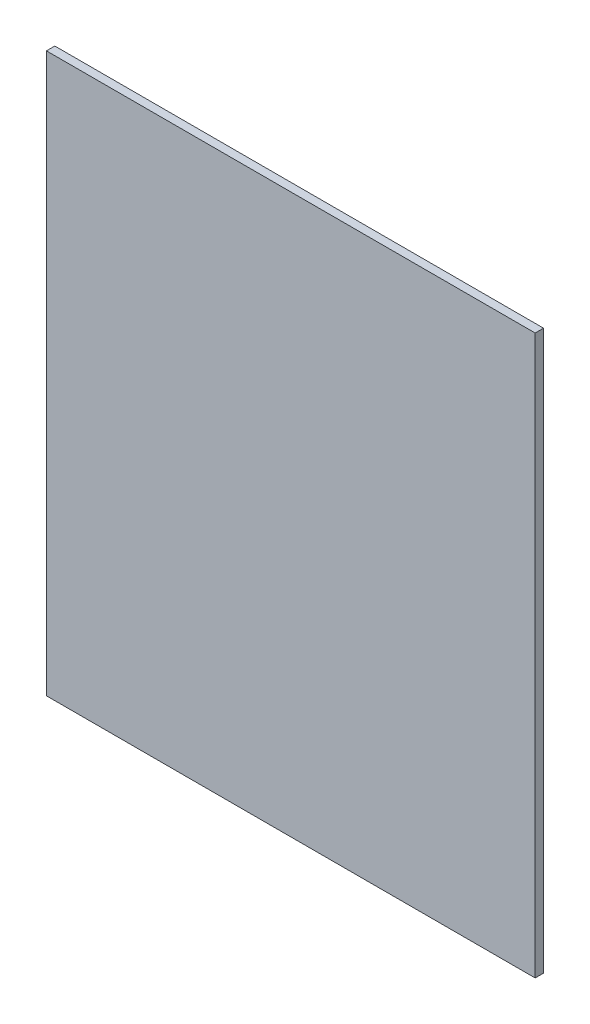
SolidWorks part; units mm, degrees
material "PET"
ref_plane "Front Plane" through (0, 0, 0) normal (0, 0, 1) x (1, 0, 0)
ref_plane "Top Plane" through (0, 0, 0) normal (0, 1, 0) x (1, 0, 0)
ref_plane "Right Plane" through (0, 0, 0) normal (1, 0, 0) x (0, 0, -1)
sketch "Sketch1" plane through (0, 0, 0) normal (0, 0, 1) x (1, 0, 0)
  line L1 (-28.5714, 377.1048) -> (321.4286, 377.1048)
  line L2 (-28.5714, 377.1048) -> (-28.5714, -22.8952)
  line L3 (-28.5714, -22.8952) -> (321.4286, -22.8952)
  line L4 (321.4286, 377.1048) -> (321.4286, -22.8952)
  dimension "D1" = 400
  dimension "D2" = 350
extrude "Boss-Extrude1" add sketch "Sketch1" along normal blind 6
